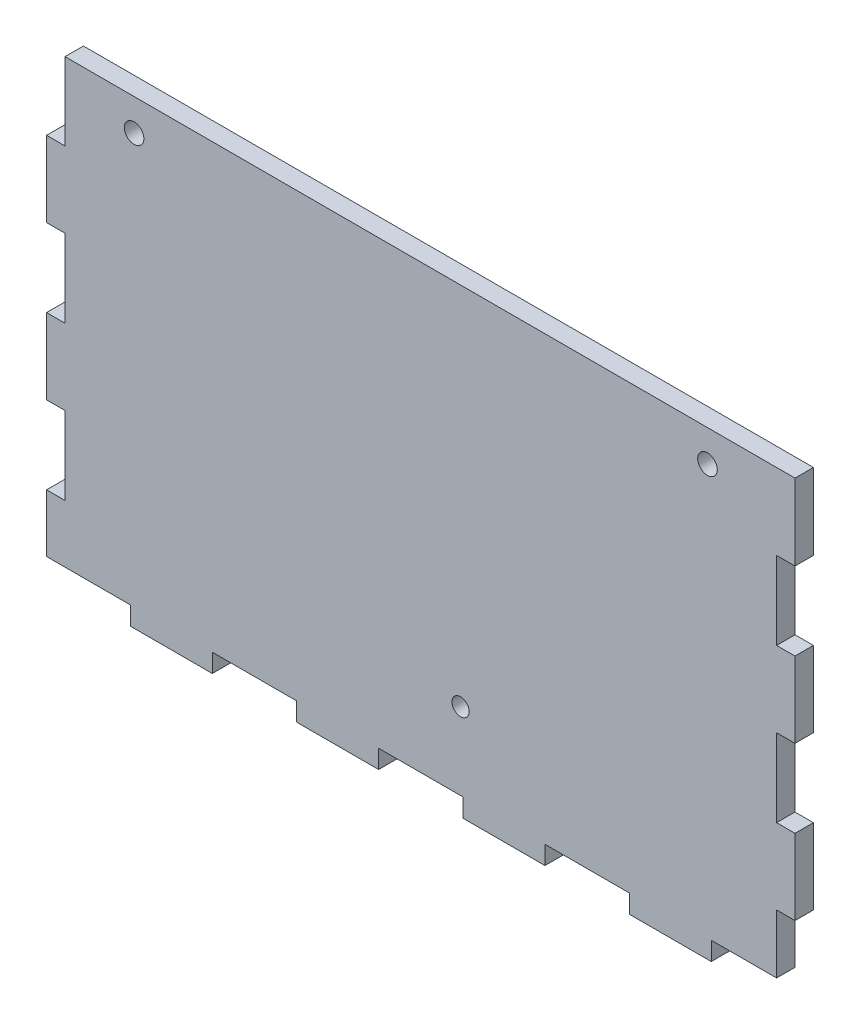
SolidWorks part; units mm, degrees
ref_plane "Front Plane" through (0, 0, 0) normal (0, 0, 1) x (1, 0, 0)
ref_plane "Top Plane" through (0, 0, 0) normal (0, 1, 0) x (1, 0, 0)
ref_plane "Right Plane" through (0, 0, 0) normal (1, 0, 0) x (0, 0, -1)
sketch "Sketch1" plane through (0, 0, 0) normal (0, 0, 1) x (1, 0, 0)
  line L1 (0, 0) -> (130, 0)
  line L2 (0, 0) -> (0, 80)
  line L3 (0, 80) -> (130, 80)
  line L4 (130, 0) -> (130, 80)
  dimension "D1" = 130
  dimension "D2" = 80
extrude "Boss-Extrude1" add sketch "Sketch1" along normal blind 3.2
sketch "Sketch2" plane through (0, 0, 3.2) normal (0, 0, 1) x (1, 0, 0)
  line L61 (14.4444, 3.2) -> (28.8889, 3.2) construction
  line L62 (0, 0) -> (14.4444, 0)
  line L67 (0, 0) -> (0, 3.2)
  line L72 (0, 3.2) -> (14.4444, 3.2)
  line L77 (14.4444, 0) -> (14.4444, 3.2)
  line L97 (28.8889, 0) -> (28.8889, 3.2)
  line L98 (28.8889, 0) -> (43.3333, 0)
  line L107 (43.3333, 0) -> (43.3333, 3.2)
  line L115 (28.8889, 3.2) -> (43.3333, 3.2)
  line L117 (43.3333, 3.2) -> (57.7778, 3.2) construction
  line L123 (57.7778, 0) -> (57.7778, 3.2)
  line L128 (57.7778, 0) -> (72.2222, 0)
  line L129 (72.2222, 0) -> (72.2222, 3.2)
  line L131 (57.7778, 3.2) -> (72.2222, 3.2)
  line L132 (72.2222, 3.2) -> (86.6667, 3.2) construction
  line L133 (86.6667, 0) -> (86.6667, 3.2)
  line L134 (86.6667, 0) -> (101.1111, 0)
  line L135 (101.1111, 0) -> (101.1111, 3.2)
  line L136 (86.6667, 3.2) -> (101.1111, 3.2)
  line L137 (101.1111, 3.2) -> (115.5556, 3.2) construction
  line L138 (115.5556, 0) -> (115.5556, 3.2)
  line L139 (115.5556, 0) -> (130, 0)
  line L142 (130, 0) -> (130, 80) construction
  line L143 (0, 80) -> (0, 0) construction
  line L144 (0, 13.3333) -> (3.2, 13.3333)
  line L145 (0, 13.3333) -> (0, 26.6667)
  line L146 (130, 3.2) -> (144.4444, 3.2) construction
  line L147 (0, 26.6667) -> (3.2, 26.6667)
  line L148 (3.2, 13.3333) -> (3.2, 26.6667)
  line L149 (3.2, 13.3333) -> (3.2, 0) construction
  line L150 (0, 40) -> (0, 53.3333)
  line L151 (0, 40) -> (3.2, 40)
  line L152 (3.2, 40) -> (3.2, 53.3333)
  line L153 (0, 53.3333) -> (3.2, 53.3333)
  line L154 (3.2, 40) -> (3.2, 26.6667) construction
  line L155 (0, 66.6667) -> (0, 80)
  line L156 (0, 66.6667) -> (3.2, 66.6667)
  line L157 (3.2, 66.6667) -> (3.2, 80)
  line L158 (0, 80) -> (3.2, 80)
  line L159 (3.2, 66.6667) -> (3.2, 53.3333) construction
  line L160 (130, 80) -> (0, 80) construction
  line L161 (126.8, 80) -> (126.8, 66.6667) construction
  line L162 (126.8, 40) -> (126.8, 26.6667)
  line L163 (126.8, 66.6667) -> (130, 66.6667)
  line L164 (126.8, 66.6667) -> (126.8, 53.3333)
  line L165 (126.8, 53.3333) -> (130, 53.3333)
  line L166 (130, 66.6667) -> (130, 53.3333)
  line L167 (126.8, 40) -> (130, 40)
  line L168 (130, 40) -> (130, 26.6667)
  line L169 (126.8, 26.6667) -> (130, 26.6667)
  line L170 (126.8, 53.3333) -> (126.8, 40) construction
  line L172 (126.8, 13.3333) -> (130, 13.3333)
  line L173 (130, 13.3333) -> (130, 0)
  line L175 (126.8, 26.6667) -> (126.8, 13.3333) construction
  line L183 (115.5556, 3.2) -> (130, 3.2) [skipped]
  line L184 (130, 0) -> (130, 3.2) [skipped]
  line L185 (126.8, 13.3333) -> (126.8, 3.2)
  line L186 (126.8, 3.2) -> (115.5556, 3.2)
  line L187 (126.8, 0) -> (130, 0) [skipped]
  line L188 (126.8, 13.3333) -> (126.8, 0) [skipped]
  dimension "D2" = 3.2
  dimension "D4" = 3.2
  dimension "D6" = 3.2
  dimension "D1" = 5
  dimension "D3" = 3
  dimension "D5" = 3
extrude "Cut-Extrude1" cut sketch "Sketch2" against normal through all
other "Move Face1" face at (128.4, 53.3333, 1.6) face at (128.4, 26.6667, 1.6) face at (128.4, 13.3333, 1.6) face at (128.4, 40, 1.6) face at (128.4, 66.6667, 1.6) face at (115.5556, 1.6, 1.6) face at (86.6667, 1.6, 1.6) face at (57.7778, 1.6, 1.6) face at (28.8889, 1.6, 1.6) face at (14.4444, 1.6, 1.6) face at (43.3333, 1.6, 1.6) face at (72.2222, 1.6, 1.6) face at (101.1111, 1.6, 1.6) face at (1.6, 26.6667, 1.6) face at (1.6, 13.3333, 1.6) face at (1.6, 40, 1.6) face at (1.6, 53.3333, 1.6) face at (1.6, 66.6667, 1.6) parameters "D1"=0.1
sketch "Sketch3" plane through (0, 0, 3.2) normal (0, 0, 1) x (1, 0, 0)
  line L0 (0, 66.5667) -> (0, 53.4333) construction
  line L1 (130, 80) -> (3.2, 80) construction
  line L2 (0, 66.5667) -> (130, 66.7667) construction
  line L3 (65, 66.6667) -> (65, 50066.6667) construction
  circle A0 centre (15.2, 74.5) radius 1.7
  circle A1 centre (114.8, 74.5) radius 1.7
  point P10 (65, 66.6667)
  dimension "D1" = 3.4
  dimension "D2" = 15.2
  dimension "D3" = 5.5
extrude "Cut-Extrude2" cut sketch "Sketch3" against normal up to next
sketch "Sketch4" plane through (0, 0, 0) normal (0, 0, -1) x (-1, 0, 0)
  line L0 (-130, 13.4333) -> (-130, 26.5667) construction
  line L4 (-72.3222, 3.2) -> (-57.6778, 3.2) construction
  circle A0 centre (-71.91, 16.56) radius 1.5
  dimension "D2" = 3
  dimension "D1" = 58.09
  dimension "D3" = 13.36
extrude "Cut-Extrude3" cut sketch "Sketch4" against normal up to next
equation "\"wall_thickness\"= 3.2mm"
equation "\"D1@Boss-Extrude1\"=\"wall_thickness\""
equation "\"slot_width_tolerance\"= 0.1mm"
equation "\"slot_depth\"= 3.2mm"
equation "\"D2@Sketch2\"=\"slot_depth\""
equation "\"D4@Sketch2\"=\"slot_depth\""
equation "\"D6@Sketch2\"=\"slot_depth\""
equation "\"D2@Sketch3\"=12.00mm+\"slot_depth\""
